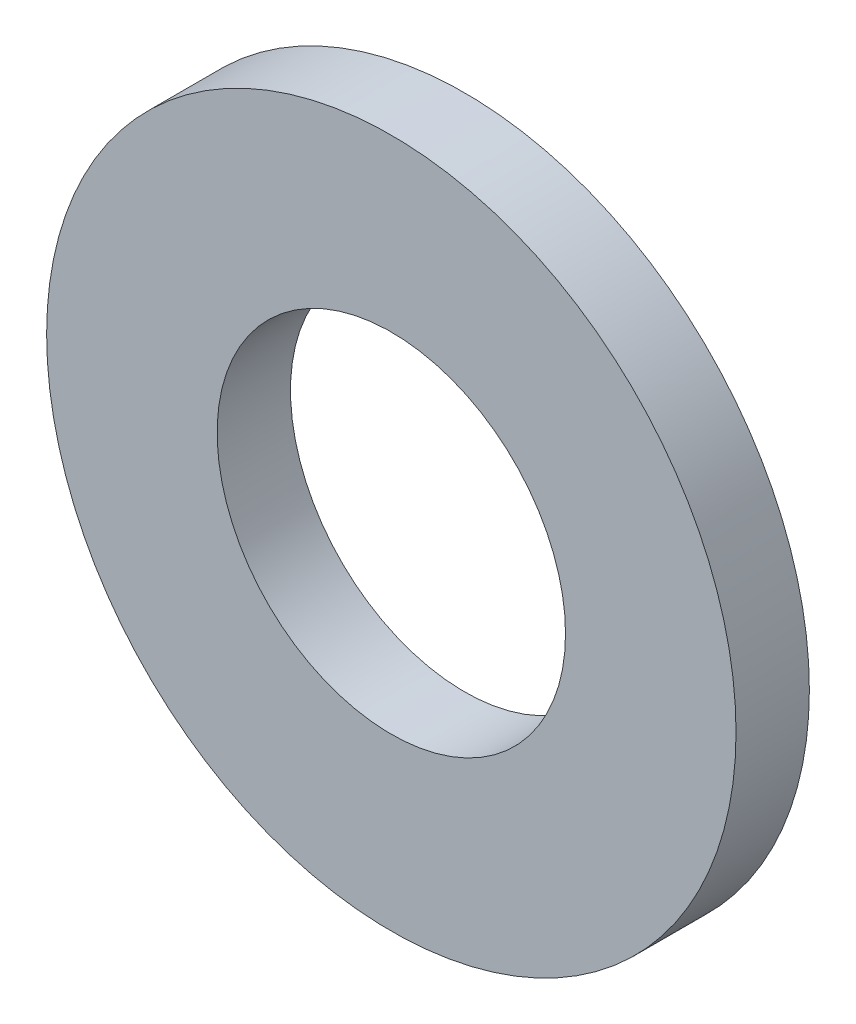
SolidWorks part; units mm, degrees
ref_plane "Plan de face" through (0, 0, 0) normal (0, 0, 1) x (1, 0, 0)
ref_plane "Plan de dessus" through (0, 0, 0) normal (0, 1, 0) x (1, 0, 0)
ref_plane "Plan de droite" through (0, 0, 0) normal (1, 0, 0) x (0, 0, -1)
sketch "Sketch1" plane through (0, 0, 0) normal (0, 0, 1) x (1, 0, 0)
  circle A0 centre (0, 0) radius 4.75
  circle A1 centre (0, 0) radius 9.4
  dimension "D1" = 18.8
  dimension "D2" = 9.5
extrude "Boss-Extrude1" add sketch "Sketch1" against normal blind 2
